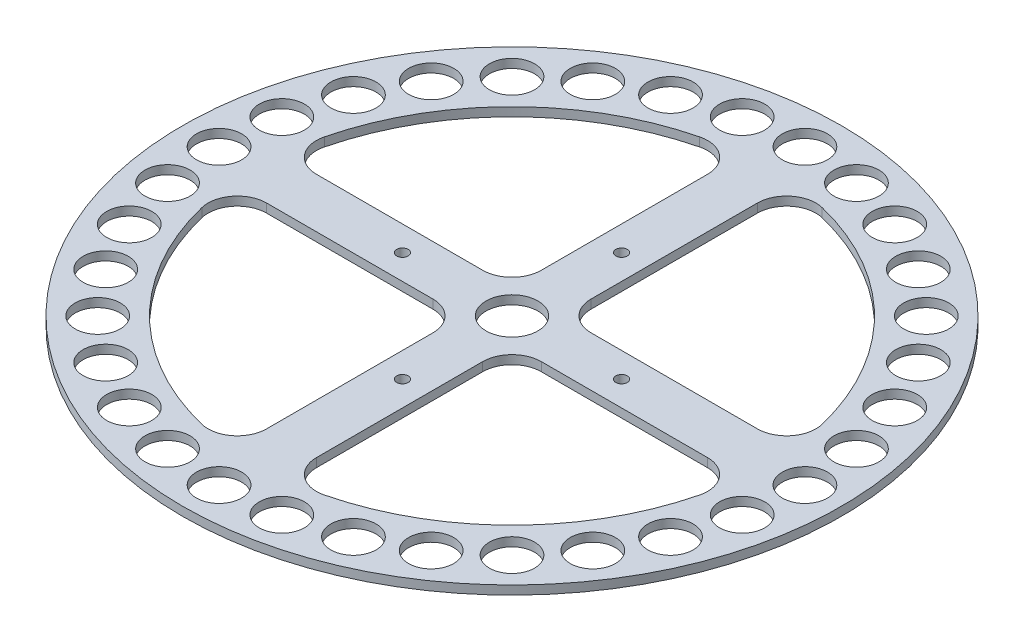
SolidWorks part; units mm, degrees
ref_plane "Front Plane" through (0, 0, 0) normal (0, 0, 1) x (1, 0, 0)
ref_plane "Top Plane" through (0, 0, 0) normal (0, 1, 0) x (1, 0, 0)
ref_plane "Right Plane" through (0, 0, 0) normal (1, 0, 0) x (0, 0, -1)
sketch "Sketch1" plane through (0, 0, 0) normal (0, 1, 0) x (1, 0, 0)
  circle A0 centre (0, 0) radius 142.875
  circle A4 centre (0, 0) radius 11.25
  point P6 (0, 0)
  dimension "D1" = 285.75
  dimension "D2" = 22.5
extrude "Boss-Extrude2" add sketch "Sketch1" against normal blind 3.81
sketch "Sketch2" plane through (0, 0, 0) normal (0, 1, 0) x (1, 0, 0)
  line L2 (-142.875, 0) -> (142.875, 0) construction
  circle A5 centre (0, 0) radius 142.875 construction
  circle A9 centre (-127, 0) radius 9.779
  circle A10 centre (0, 0) radius 117.221 construction
  dimension "D1" = 19.558
  dimension "D2" = 127
  dimension "D3" = 234.442
extrude "Cut-Extrude1" cut sketch "Sketch2" against normal through all
sketch "Sketch4" plane through (0, 0, 0) normal (0, 1, 0) x (1, 0, 0)
  line L0 (-10.795, 16.3468) -> (-10.795, 110.5994)
  line L7 (10.795, 13.385) -> (10.795, 110.5994)
  line L8 (-13.3205, 10.795) -> (-10.795, 10.795)
  line L9 (-10.795, 10.795) -> (-10.795, 16.3468)
  line L10 (10.795, 13.385) -> (10.795, 10.795)
  line L11 (14.5573, 10.795) -> (110.5994, 10.795)
  line L13 (14.3306, -10.795) -> (110.5994, -10.795)
  line L15 (10.795, -14.2763) -> (10.795, -110.5994)
  line L17 (-10.795, -14.0687) -> (-10.795, -110.5994)
  line L19 (-15.5509, -10.795) -> (-110.5994, -10.795)
  line L21 (-13.3205, 10.795) -> (-110.5994, 10.795)
  line L23 (10.795, 10.795) -> (14.5573, 10.795)
  line L24 (-15.5509, -10.795) -> (-10.795, -10.795)
  line L25 (10.795, -14.2763) -> (10.795, -10.795)
  line L27 (10.795, -10.795) -> (14.3306, -10.795)
  line L28 (-10.795, -14.0687) -> (-10.795, -10.795)
  circle A0 centre (0, 0) radius 111.125
  circle A2 centre (0, 0) radius 11.25 construction
  point P4 (0, 50.5441)
  point P25 (0, 0)
  dimension "D1" = 222.25
  dimension "D5" = 10.795
  dimension "D2" = 21.59
  dimension "D3" = 10.795
  dimension "D6" = 10.795
  dimension "D7" = 10.795
  dimension "D8" = 21.59
  dimension "D9" = 10.795
  dimension "D10" = 21.59
  dimension "D11" = 21.59
  dimension "D12" = 10.795
  dimension "D13" = 10.795
  dimension "D14" = 10.795
  dimension "D4" = 4
extrude "Cut-Extrude2" cut sketch "Sketch4" against normal through all and the other way through all
fillet "Fillet1" radius 12.7 12 edges at (-110.5994, -1.905, 10.795) (-10.795, -1.905, 110.5994) (10.795, -1.905, 110.5994) (110.5994, -1.905, 10.795) (110.5994, -1.905, -10.795) (10.795, -1.905, -110.5994) (-10.795, -1.905, -110.5994) (-110.5994, -1.905, -10.795) (-10.795, -1.905, -10.795) (10.795, -1.905, -10.795) (10.795, -1.905, 10.795) (-10.795, -1.905, 10.795)
sketch "Sketch5" plane through (0, 0, 0) normal (0, 1, 0) x (1, 0, 0)
  line L0 (0, 142.875) -> (0, -142.875) construction
  line L1 (-142.875, 0) -> (142.875, 0) construction
  circle A0 centre (0, 0) radius 142.875 construction
  circle A1 centre (0, 47.5) radius 2.5
  circle A2 centre (47.5, 0) radius 2.5
  circle A3 centre (0, -47.5) radius 2.5
  circle A4 centre (-47.5, 0) radius 2.5
  point P19 (0, 0)
  dimension "D1" = 5
  dimension "D2" = 47.5
  dimension "D3" = 4
pattern_circular "CirPattern1" count 32 over 360 about axis through (0, 0, 0) along (0, 1, 0) of "Cut-Extrude1"
extrude "Cut-Extrude3" cut sketch "Sketch5" against normal through all contours A1 | A2 | A3 | A4
